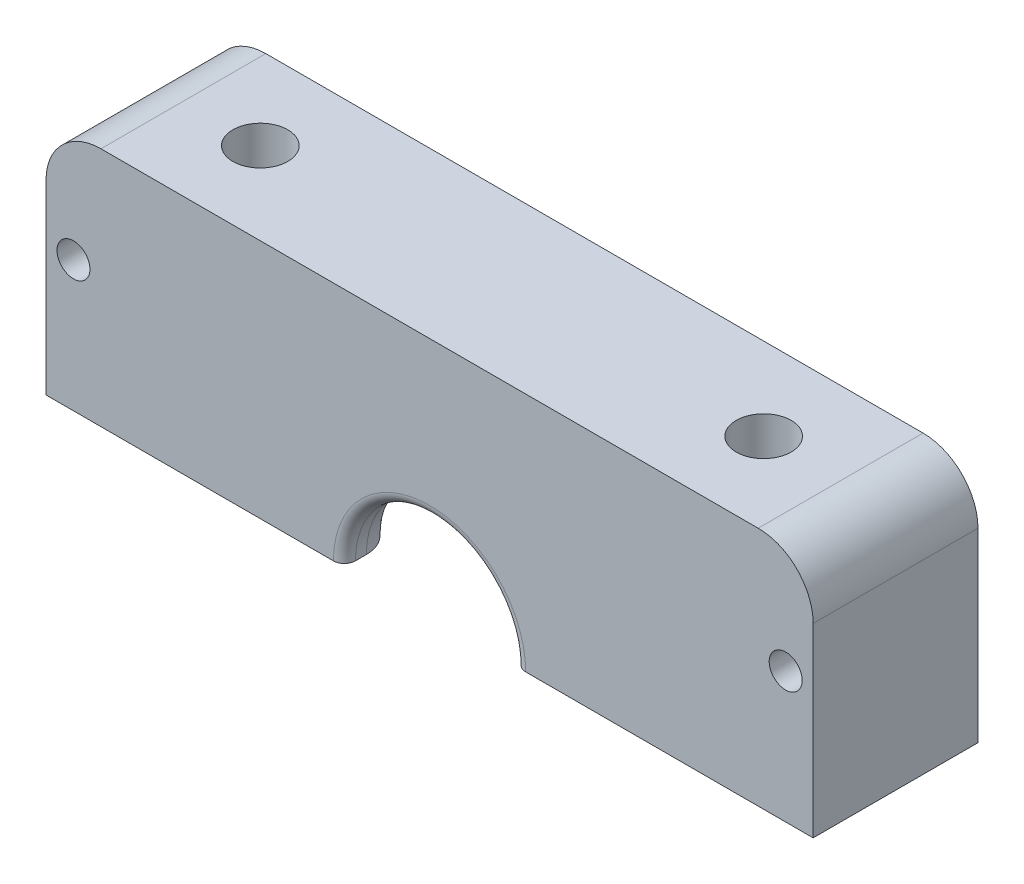
SolidWorks part; units mm, degrees
ref_plane "前基準面" through (0, 0, 0) normal (0, 0, 1) x (1, 0, 0)
ref_plane "上基準面" through (0, 0, 0) normal (0, 1, 0) x (1, 0, 0)
ref_plane "右基準面" through (0, 0, 0) normal (1, 0, 0) x (0, 0, -1)
sketch "草圖1" plane through (0, 0, 0) normal (0, 0, 1) x (1, 0, 0)
  line L1 (-29.9, 21.9) -> (29.9, 21.9)
  line L2 (-34.9, 16.9) -> (-34.9, -16.9)
  line L3 (-29.9, -21.9) -> (29.9, -21.9)
  line L4 (34.9, 16.9) -> (34.9, -16.9)
  line L5 (-34.9, 21.9) -> (34.9, -21.9) construction
  line L6 (-34.9, -21.9) -> (34.9, 21.9) construction
  arc A0 (-34.9, -16.9) -> (-29.9, -21.9) centre (-29.9, -16.9) ccw
  arc A1 (29.9, -21.9) -> (34.9, -16.9) centre (29.9, -16.9) ccw
  arc A2 (29.9, 21.9) -> (34.9, 16.9) centre (29.9, 16.9) cw
  arc A3 (-29.9, 21.9) -> (-34.9, 16.9) centre (-29.9, 16.9) ccw
  point P0 (0, 0)
  dimension "D3" = 5
  dimension "D1" = 69.8
  dimension "D2" = 43.8
extrude "填料-伸長1" add sketch "草圖1" along normal blind 15
sketch "草圖2" plane through (0, 0, 15) normal (0, 0, 1) x (1, 0, 0)
  line L0 (0, 21.9) -> (0, -21.9) construction
  line L1 (29.9, 21.9) -> (-29.9, 21.9) construction
  line L2 (-29.9, -21.9) -> (29.9, -21.9) construction
  line L3 (-34.9, 16.9) -> (-34.9, -16.9) construction
  line L4 (-34.9, 0) -> (34.9, 0) construction
  line L5 (34.9, -16.9) -> (34.9, 16.9) construction
  circle A0 centre (-32.4, 11.9) radius 1.5
  circle A1 centre (-32.4, -11.9) radius 1.5
  circle A2 centre (32.4, -11.9) radius 1.5
  circle A3 centre (32.4, 11.9) radius 1.5
  dimension "D1" = 2.5
  dimension "D3" = 3
  dimension "D2" = 10
extrude "除料-伸長1" cut sketch "草圖2" against normal through all
sketch "草圖3" plane through (0, 0, 15) normal (0, 0, 1) x (1, 0, 0)
  circle A0 centre (0, 0) radius 7.75
  dimension "D1" = 15.5
extrude "除料-伸長2" cut sketch "草圖3" against normal blind 5
sketch "草圖4" plane through (0, 0, 0) normal (0, 1, 0) x (1, 0, 0)
  line L0 (0, -15) -> (0, 0) construction
  line L1 (-7.75, -15) -> (7.75, -15) construction
  line L2 (29.9, 0) -> (-29.9, 0) construction
  line L3 (0, -4.5) -> (-15.5, -4.5)
  line L4 (-15.5, -4.5) -> (-15.5, -10)
  line L5 (-15.5, -10) -> (0, -10)
  line L6 (0, -10) -> (0, -4.5)
  line L7 (29.9, -15) -> (-29.9, -15) construction
  dimension "D1" = 5.5
  dimension "D2" = 15.5
  dimension "D3" = 5
revolve "除料-旋轉1" cut sketch "草圖4" angle 360 about L0
sketch "草圖5" plane through (0, 0, 15) normal (0, 0, 1) x (1, 0, 0)
  line L0 (-43.4263, 0) -> (45.2264, 0)
  line L1 (45.2264, 0) -> (45.2264, -26.5133)
  line L2 (45.2264, -26.5133) -> (-43.4263, -26.5133)
  line L3 (-43.4263, -26.5133) -> (-43.4263, 0)
extrude "除料-伸長3" cut sketch "草圖5" against normal through all
sketch "草圖6" plane through (0, 21.9, 0) normal (0, 1, 0) x (1, 0, 0)
  line L0 (0, 0) -> (0, -15) construction
  line L1 (29.9, -15) -> (-29.9, -15) construction
  line L2 (-29.9, -15) -> (-29.9, 0) construction
  circle A0 centre (-22.9, -7.5) radius 2.5
  circle A1 centre (22.9, -7.5) radius 2.5
  point P10 (-29.9, -7.5)
  dimension "D1" = 7
  dimension "D2" = 5
extrude "除料-伸長4" cut sketch "草圖6" against normal through all
fillet "圓角3" radius 1 2 edges at (0, 15.5, 4.5) (0, 15.5, 10)
fillet "圓角4" radius 1 1 edges at (0, 7.75, 15)
fillet "圓角5" radius 3 1 edges at (0, 7.75, 10)
